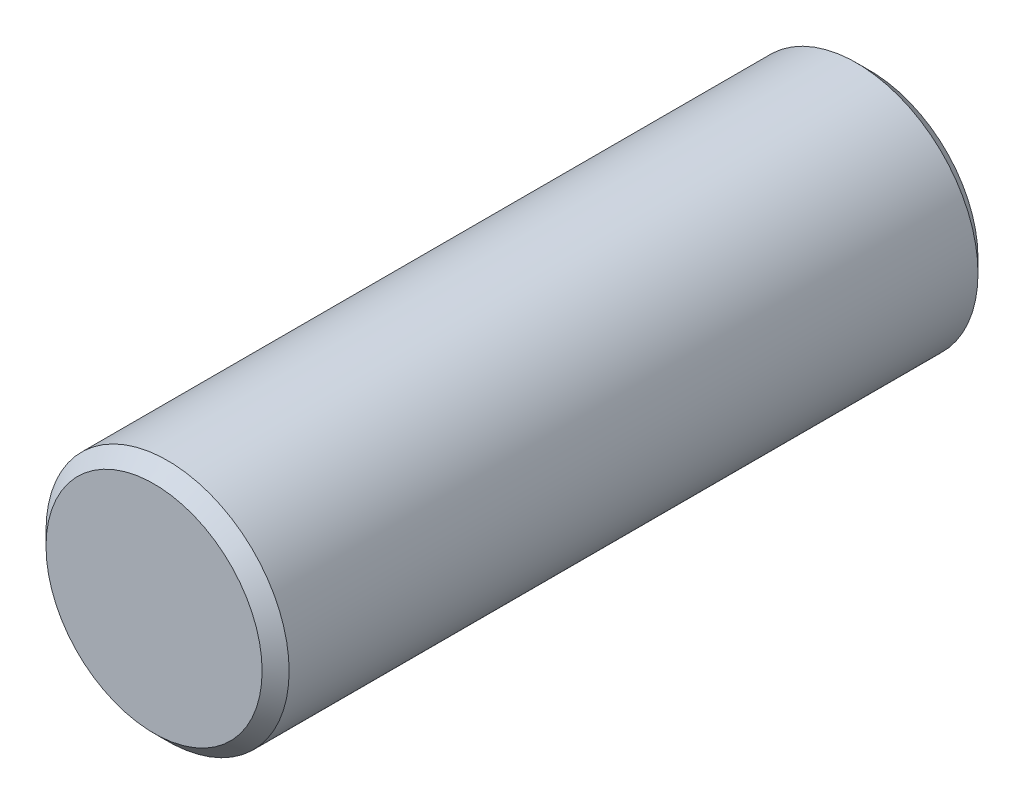
SolidWorks part; units mm, degrees
ref_plane "Ön Düzlem" through (0, 0, 0) normal (0, 0, 1) x (1, 0, 0)
ref_plane "Üst Düzlem" through (0, 0, 0) normal (0, 1, 0) x (1, 0, 0)
ref_plane "Sağ Düzlem" through (0, 0, 0) normal (1, 0, 0) x (0, 0, -1)
sketch "Çizim1" plane through (0, 0, 0) normal (0, 0, 1) x (1, 0, 0)
  circle A0 centre (0, 0) radius 9
  dimension "D1" = 18
extrude "Yükseklik-Ekstrüzyon1" add sketch "Çizim1" along normal blind 53
chamfer "Pah1" distance 1 angle 45 2 edges at (9, 0, 0) (9, 0, 53)
